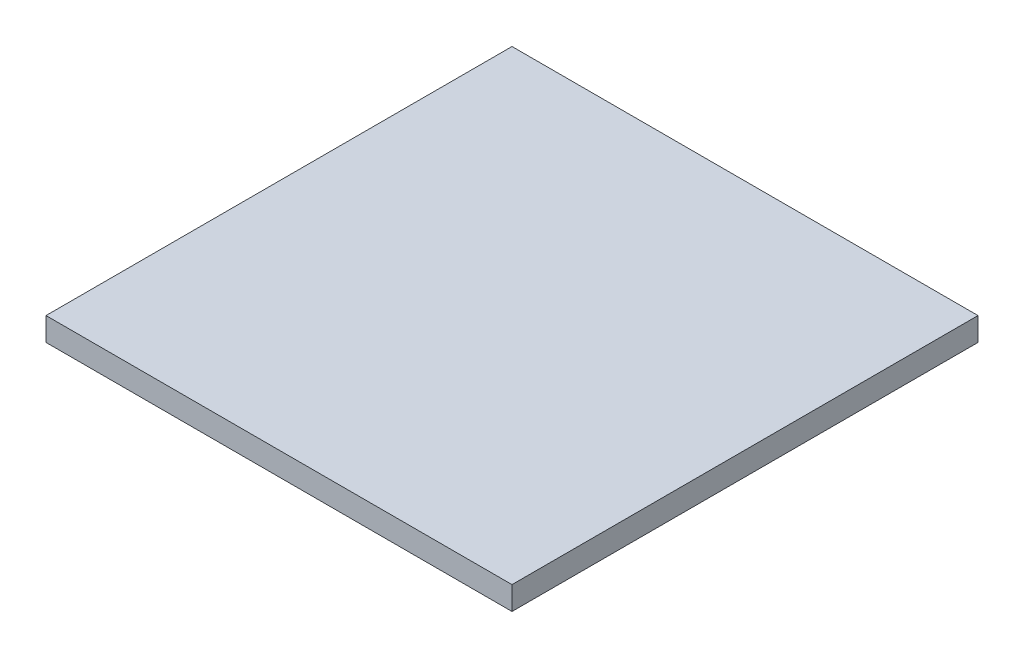
SolidWorks part; units mm, degrees
material "PCB"
ref_plane "Front Plane" through (0, 0, 0) normal (0, 0, 1) x (1, 0, 0)
ref_plane "Top Plane" through (0, 0, 0) normal (0, 1, 0) x (1, 0, 0)
ref_plane "Right Plane" through (0, 0, 0) normal (1, 0, 0) x (0, 0, -1)
sketch "Sketch1" plane through (0, 0, 0) normal (0, 1, 0) x (1, 0, 0)
  line L1 (0, 0) -> (30, 0)
  line L2 (0, 0) -> (0, 30)
  line L3 (0, 30) -> (30, 30)
  line L4 (30, 0) -> (30, 30)
  dimension "D1" = 30
  dimension "D2" = 30
extrude "Board" add sketch "Sketch1" along normal blind 1.5
sketch "Sketch2" [suppressed] plane through (0, 1.5, 0) normal (0, 1, 0) x (1, 0, 0)
  line L0 (0, 0) -> (82, 0) construction
  line L2 (0, 82) -> (0, 0) construction
  circle A0 centre (5, 5) radius 1.75
  circle A1 centre (77, 5) radius 1.75
  circle A2 centre (5, 77) radius 1.75
  circle A3 centre (77, 77) radius 1.75
  dimension "D3" = 3.5
  dimension "D1" = 5
  dimension "D2" = 5
  dimension "D4" = 2
  dimension "D5" = 2
extrude "Mounting Holes" [suppressed] cut sketch "Sketch2" against normal through all
